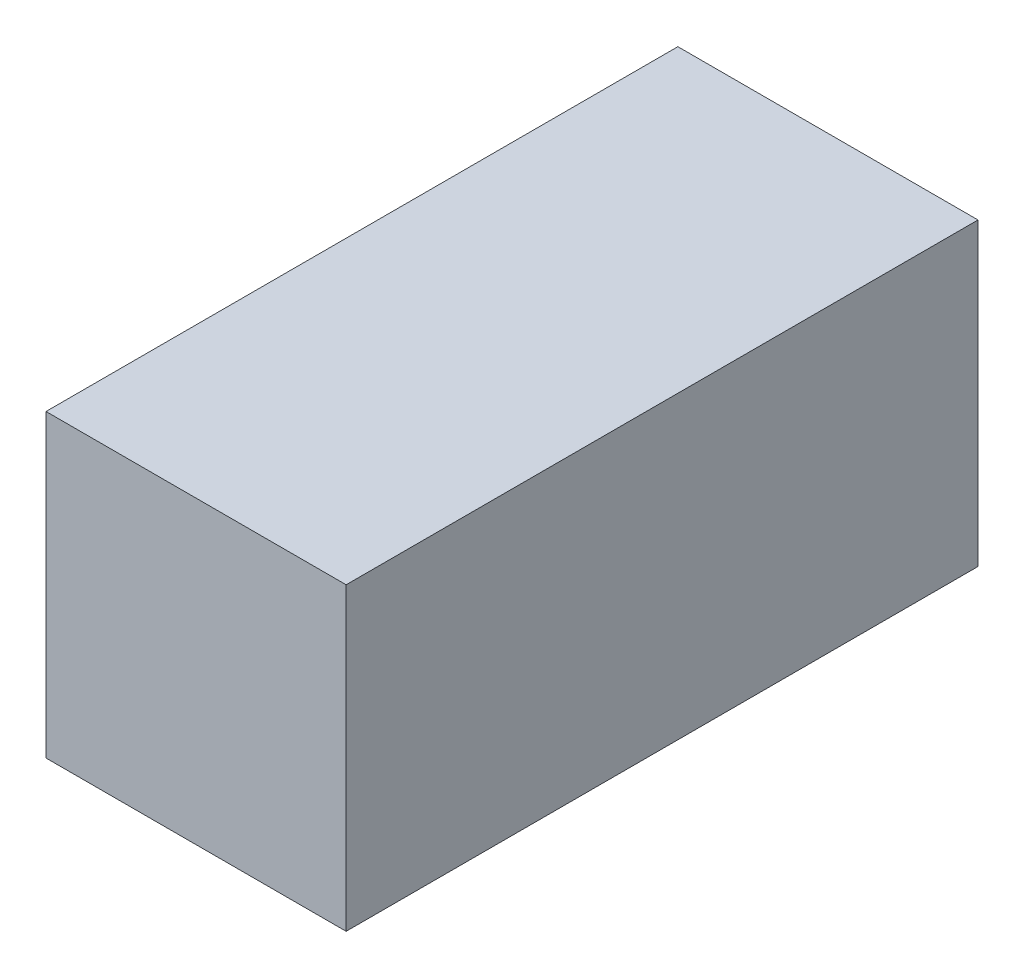
SolidWorks part; units mm, degrees
ref_plane "Спереди" through (0, 0, 0) normal (0, 0, 1) x (1, 0, 0)
ref_plane "Сверху" through (0, 0, 0) normal (0, 1, 0) x (1, 0, 0)
ref_plane "Справа" through (0, 0, 0) normal (1, 0, 0) x (0, 0, -1)
sketch "Эскиз1" plane through (0, 0, 0) normal (0, 0, 1) x (1, 0, 0)
  line L1 (-6.65, 6.65) -> (6.65, 6.65)
  line L2 (-6.65, 6.65) -> (-6.65, -6.65)
  line L3 (-6.65, -6.65) -> (6.65, -6.65)
  line L4 (6.65, 6.65) -> (6.65, -6.65)
  line L5 (-6.65, 6.65) -> (6.65, -6.65) construction
  line L6 (-6.65, -6.65) -> (6.65, 6.65) construction
  point P0 (0, 0)
  dimension "D1" = 13.3
extrude "Бобышка-Вытянуть1" add sketch "Эскиз1" along normal blind 28
sketch "Эскиз2" plane through (0, 6.65, 0) normal (0, 1, 0) x (1, 0, 0)
  line L0 (0, 0) -> (0, -28) construction
  line L1 (6.65, -28) -> (-6.65, -28) construction
  line L2 (6.65, 0) -> (-6.65, 0) construction
  circle A0 centre (0, -7.7) radius 1.65
  circle A1 centre (0, -22.7) radius 1.65
  dimension "D1" = 3.3
  dimension "D2" = 7.7
  dimension "D3" = 15
extrude "Вырез-Вытянуть1" [suppressed] cut sketch "Эскиз2" against normal through all
